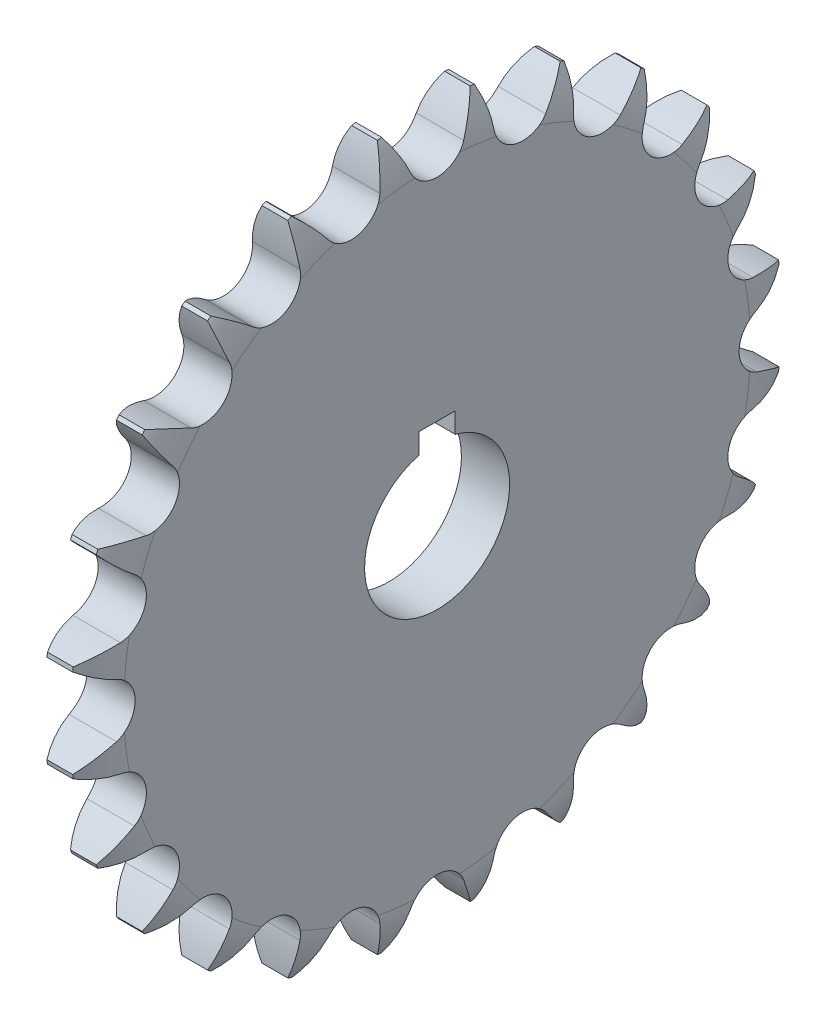
SolidWorks part; units mm, degrees
ref_plane "Plane1" through (0, 0, 0) normal (0, 0, 1) x (1, 0, 0)
ref_plane "Plane2" through (0, 0, 0) normal (0, 1, 0) x (1, 0, 0)
ref_plane "Plane3" through (0, 0, 0) normal (1, 0, 0) x (0, 0, -1)
sketch "Clipboard" plane through (0, 0, 0) normal (0, 1, 0) x (1, 0, 0)
  line L0 (0, 0) -> (8.7015, -3.8742)
  line L1 (-15, 0) -> (100, 0) construction
  line L2 (0, 0) -> (-0.8203, 0.9272)
  line L3 (0, 0) -> (-8.8973, 3.4006)
  line L4 (0, 0) -> (2.832, 1.2609)
  line L5 (0, 0) -> (-46.8476, -17.4728)
  line L6 (0, 0) -> (-4.4098, -2.9753)
  line L7 (-0.8203, 0.9272) -> (44.4955, 22.0583)
  line L8 (-76.2, 38.1) -> (-74.4, 38.1)
  line L9 (-73.3242, 40.7328) -> (-72.926, 40.7699)
  line L10 (-73.4529, 9.1872) -> (-63.2129, 9.1872)
  circle A0 centre (0, 0) radius 3.175
  circle A1 centre (0, 0) radius 31.4996
  circle A2 centre (0, 0) radius 37.5
  dimension "Dr" = 6.35
  dimension "MHD" = 62.9992
  dimension "Hub_dia" = 75
  dimension "Num_teeth" = 24
  dimension "Pitch" = 9.525
  dimension "Width" = 3.1
  dimension "Side_relief" = 1.238
  dimension "Side_radius" = 9.525
  dimension "Overall_len" = 50
  dimension "Show_teeth" = 24
  dimension "Thickness" = 5.3196
  dimension "OAL" = 50.0005
  dimension "T_dim" = 1.8
  dimension "Fillet_rad" = 0.4
  dimension "Face_width" = 5.32
  dimension "Num_strands" = 1
  dimension "Transv_pitch" = 10.24
  dimension "Plate_wid" = 8.26
sketch "BasProSke" plane through (0, 0, 0) normal (0, 1, 0) x (1, 0, 0)
  line L0 (-10, 0) -> (60, 0) construction
  line L1 (0, 0) -> (0, 34.5692)
  line L2 (0, 0) -> (5.3196, 0)
  line L3 (5.3196, 0) -> (5.3196, 34.5692)
  line L4 (4.0816, 39.2651) -> (1.238, 39.2651)
  arc A0 (0, 34.5692) -> (1.238, 39.2651) centre (9.525, 34.5692) cw
  arc A1 (5.3196, 34.5692) -> (4.0816, 39.2651) centre (-4.2054, 34.5692) ccw
  dimension "Thickness" = 5.3196
  dimension "D1" = 9.525
  dimension "G1" = 1.238
  dimension "G2" = 1.238
  dimension "Diameter" = 78.5301
revolve "Base-Revolve" add sketch "BasProSke" angle 360 about L0
sketch "TooCutSke" plane through (0, 0, 0) normal (1, 0, 0) x (0, 0, -1)
  line L0 (0, 36.5187) -> (2.9759, 35.3239) construction
  line L1 (0, 0) -> (0, 107) construction
  line L2 (0, 36.5187) -> (-10, 36.5187) construction
  line L3 (0, 36.5187) -> (-2.9759, 35.3239) construction
  arc A0 (2.9759, 35.3239) -> (5.214, 39.4217) centre (21.3614, 27.9423) cw
  arc A1 (2.9759, 35.3239) -> (-2.9759, 35.3239) centre (0, 36.5187) cw
  arc A2 (-2.9759, 35.3239) -> (-5.214, 39.4217) centre (-21.3614, 27.9423) ccw
  arc A3 (5.214, 39.4217) -> (-5.214, 39.4217) centre (0, 0) ccw
  dimension "R1" = 3.2067
  dimension "R2" = 19.812
  dimension "Overcut" = 39.7651
  dimension "Seat_radius" = 36.5187
  dimension "X" = 136.25
extrude "ToothCut" cut sketch "TooCutSke" along normal through all
pattern_circular "TeethCuts" count 24 every 15 about axis through (-10, 0, 0) along (1, 0, 0) of "ToothCut"
sketch "HubNeaOneSke" plane through (0, 0, 0) normal (-1, 0, 0) x (0, 0, 1)
  circle A0 centre (0, 0) radius 31.4996
  dimension "Diameter" = 62.9992
extrude "HubNearOne" [suppressed] add sketch "HubNeaOneSke" along normal blind 44.6809
fillet "HubNearOneFillet" [suppressed] radius 0.4
sketch "HubNeaBotSke" plane through (0, 0, 0) normal (-1, 0, 0) x (0, 0, 1)
  circle A0 centre (0, 0) radius 31.4996
  dimension "Diameter" = 62.9992
extrude "HubNearBoth" [suppressed] add sketch "HubNeaBotSke" along normal blind 22.3405
fillet "HubNearBothFillet" [suppressed] radius 0.4
ref_plane "FarPln" through (5.3196, 0, 0) normal (1, 0, 0) x (0, 0, -1)
sketch "HubFarSke" plane through (5.3196, 0, 0) normal (1, 0, 0) x (0, 0, -1)
  circle A0 centre (0, 0) radius 31.4996
  dimension "Diameter" = 62.9992
extrude "HubFar" [suppressed] add sketch "HubFarSke" along normal blind 22.3405
fillet "HubFarFillet" [suppressed] radius 0.4
sketch "BorSke" plane through (0, 0, 0) normal (1, 0, 0) x (0, 0, -1)
  circle A0 centre (0, 0) radius 5
  dimension "Diameter" = 10
extrude "Bore" cut sketch "BorSke" along normal mid plane 100.001
sketch "KeySke" plane through (0, 0, 0) normal (1, 0, 0) x (0, 0, -1)
  line L0 (-2, 0) -> (-2, 6.8)
  line L1 (-2, 6.8) -> (2, 6.8)
  line L2 (2, 6.8) -> (2, 0)
  line L3 (0, 0) -> (0, 34) construction
  line L4 (-2, 0) -> (2, 0)
  dimension "Offset" = 6.8
  dimension "Width" = 4
extrude "Keyway" [suppressed] cut sketch "KeySke" along normal mid plane 100.001
pattern_circular "Keyway2" [suppressed] count 2 every 90 about axis through (-10, 0, 0) along (1, 0, 0)
sketch "Sketch1" plane through (5.3196, 0, 0) normal (1, 0, 0) x (0, 0, -1)
  circle A0 centre (0, 0) radius 27
  circle A1 centre (0, 0) radius 6
  dimension "D1" = 54
  dimension "D2" = 12
extrude "Boss-Extrude1" add sketch "Sketch1" along normal offset from surface (22.6804 mm away) 28 up to face at (0, 0, -5)
sketch "Sketch2" plane through (28, 0, 0) normal (1, 0, 0) x (0, 0, -1)
  circle A0 centre (0, 0) radius 39.4959
extrude "trim boss" cut sketch "Sketch2" against normal up to surface (22.6804 mm away) up to face at (5.3196, 0, 27)
sketch "Sketch3" plane through (5.3196, 0, 0) normal (1, 0, 0) x (0, 0, -1)
  circle A0 centre (0, 0) radius 8
  dimension "D1" = 16
extrude "bore centre" cut sketch "Sketch3" against normal blind 20
sketch "Sketch4" plane through (0, 0, 0) normal (-1, 0, 0) x (0, 0, 1)
  line L0 (-2, 10) -> (-2, 6)
  line L1 (-2, 10) -> (2, 10)
  line L2 (-2, 6) -> (2, 6)
  line L3 (2, 10) -> (2, 6)
  line L4 (-2, 10) -> (2, 6) construction
  line L5 (-2, 6) -> (2, 10) construction
  line L6 (0, 0) -> (0, 8) construction
  circle A0 centre (0, 0) radius 8 construction
  point P1 (0, 8)
  dimension "D1" = 4
  dimension "D2" = 4
extrude "Cut-Extrude1" cut sketch "Sketch4" against normal blind 10
equation "' \"Pitch@Clipboard\" = 12.7"
equation "' \"Num_strands@Clipboard\" = 1"
equation "' \"Num_teeth@Clipboard\" = 9"
equation "' \"Hub_dia@Clipboard\" = 50"
equation "' \"Overall_len@Clipboard\" = 3"
equation "' \"Diameter@BorSke\" = 12"
equation "' \"T_dim@Clipboard\" = 1"
equation "' \"Width@KeySke\" = 2"
equation "' \"Dr@Clipboard\" = 8.51"
equation "' \"Face_width@Clipboard\" = 7.2"
equation "' \"Side_radius@Clipboard\" = 12.7"
equation "' \"Side_relief@Clipboard\" = 1.27"
equation "' \"Transv_pitch@Clipboard\" = 13.92"
equation "' \"Show_teeth@Clipboard\" = 9"
equation "' \"Fillet_rad@Clipboard\" = 0.6"
equation "' \"Plate_wid@Clipboard\" = 11.8"
equation "\"Num_teeth@Clipboard\" = int( \"Num_teeth@Clipboard\" )"
equation "\"Num_teeth@Clipboard\" = ((sgn( \"Num_teeth@Clipboard\" - 5.0)+1)*( \"Num_teeth@Clipboard\" - 5.0))/2 +5.0"
equation "\"Num_teeth@Clipboard\" = ((sgn( \"Num_teeth@Clipboard\" - 200.0)-1)*( \"Num_teeth@Clipboard\" - 200.0))/-2 +200.0"
equation "\"MHD@Clipboard\" = \"Pitch@Clipboard\" * (1.0 / tan(3.14159265 / \"Num_teeth@Clipboard\" )) - 1.04 * \"Plate_wid@Clipboard\" - 0.76"
equation "\"Thickness@Clipboard\"  = \"Face_width@Clipboard\" + (\"Num_strands@Clipboard\" - 1) * \"Transv_pitch@Clipboard\""
equation "\"OAL@Clipboard\" = \"Thickness@Clipboard\" + 2 * \"Fillet_rad@Clipboard\" + 1"
equation "\"MHD@Clipboard\" = ((sgn( \"MHD@Clipboard\" - \"Hub_dia@Clipboard\" )-1)*( \"MHD@Clipboard\" - \"Hub_dia@Clipboard\" ))/-2+ \"Hub_dia@Clipboard\""
equation "\"OAL@Clipboard\" = ((sgn( \"OAL@Clipboard\" - \"Overall_len@Clipboard\" )+1)*( \"OAL@Clipboard\" - \"Overall_len@Clipboard\" ))/2 + \"Overall_len@Clipboard\" + 0.0005"
equation "\"Num_teeth@TeethCuts\" = int( \"Show_teeth@Clipboard\" ) + 1"
equation "\"Num_teeth@TeethCuts\" = ((sgn( \"Num_teeth@TeethCuts\" - \"Num_teeth@Clipboard\" )-1)*( \"Num_teeth@TeethCuts\" - \"Num_teeth@Clipboard\" ))/-2+ \"Num_teeth@Clipboard\""
equation "\"Num_teeth@TeethCuts\" = ((sgn( \"Num_teeth@TeethCuts\" - 2.0)+1)*( \"Num_teeth@TeethCuts\" - 2.0))/2 +2.0"
equation "\"Angle@TeethCuts\" = 360.0 / \"Num_teeth@Clipboard\""
equation "\"Seat_radius@TooCutSke\" = ( \"Pitch@Clipboard\" / 2.0) / sin(3.14159265 / \"Num_teeth@Clipboard\" ) - \"Dr@Clipboard\" / 2.0 + \"Dr@Clipboard\" * 0.505"
equation "\"R1@TooCutSke\"  = \"Dr@Clipboard\" * 0.505"
equation "\"X@TooCutSke\" = 140.0 - (90.0 / \"Num_teeth@Clipboard\")"
equation "\"R2@TooCutSke\" = 0.12 * \"Dr@Clipboard\" * ( \"Num_teeth@Clipboard\" + 2.0)"
equation "\"Overcut@TooCutSke\" = 0.5 + 0.625 * \"Pitch@Clipboard\" - 0.5 * \"Dr@Clipboard\"  +  \"Pitch@Clipboard\" / 2.0 / sin(3.14159265 / \"Num_teeth@Clipboard\" )"
equation "\"Diameter@BasProSke\" = 2.0 * ( 0.625 * \"Pitch@Clipboard\" - 0.5 * \"Dr@Clipboard\"  +  \"Pitch@Clipboard\" / 2.0 / sin(3.14159265 / \"Num_teeth@Clipboard\" ))"
equation "\"Thickness@BasProSke\"  = \"Thickness@Clipboard\""
equation "\"G1@BasProSke\" =  \"Side_relief@Clipboard\""
equation "\"G2@BasProSke\" =  \"Side_relief@Clipboard\""
equation "\"D1@BasProSke\" =  \"Side_radius@Clipboard\""
equation "\"Diameter@HubNeaOneSke\" = \"MHD@Clipboard\""
equation "\"Length@HubNearOne\" = \"OAL@Clipboard\" - \"Thickness@BasProSke\""
equation "\"Diameter@HubNeaBotSke\" = \"MHD@Clipboard\""
equation "\"Length@HubNearBoth\" = ( \"OAL@Clipboard\" - \"Thickness@BasProSke\" ) / 2.0"
equation "\"D1@HubNearOneFillet\" = \"Fillet_rad@Clipboard\""
equation "\"D1@HubNearBothFillet\" = \"Fillet_rad@Clipboard\""
equation "\"Thickness@FarPln\" = \"Thickness@BasProSke\""
equation "\"Diameter@HubFarSke\" = \"MHD@Clipboard\""
equation "\"Length@HubFar\" = ( \"OAL@Clipboard\" - \"Thickness@BasProSke\" ) / 2.0"
equation "\"D1@HubFarFillet\" = \"Fillet_rad@Clipboard\""
equation "\"D1@Bore\" = \"OAL@Clipboard\" * 2.0"
equation "\"D1@Keyway\" = \"OAL@Clipboard\" * 2.0"
equation "\"Offset@KeySke\" = \"T_dim@Clipboard\" + \"Diameter@BorSke\" / 2.0"
